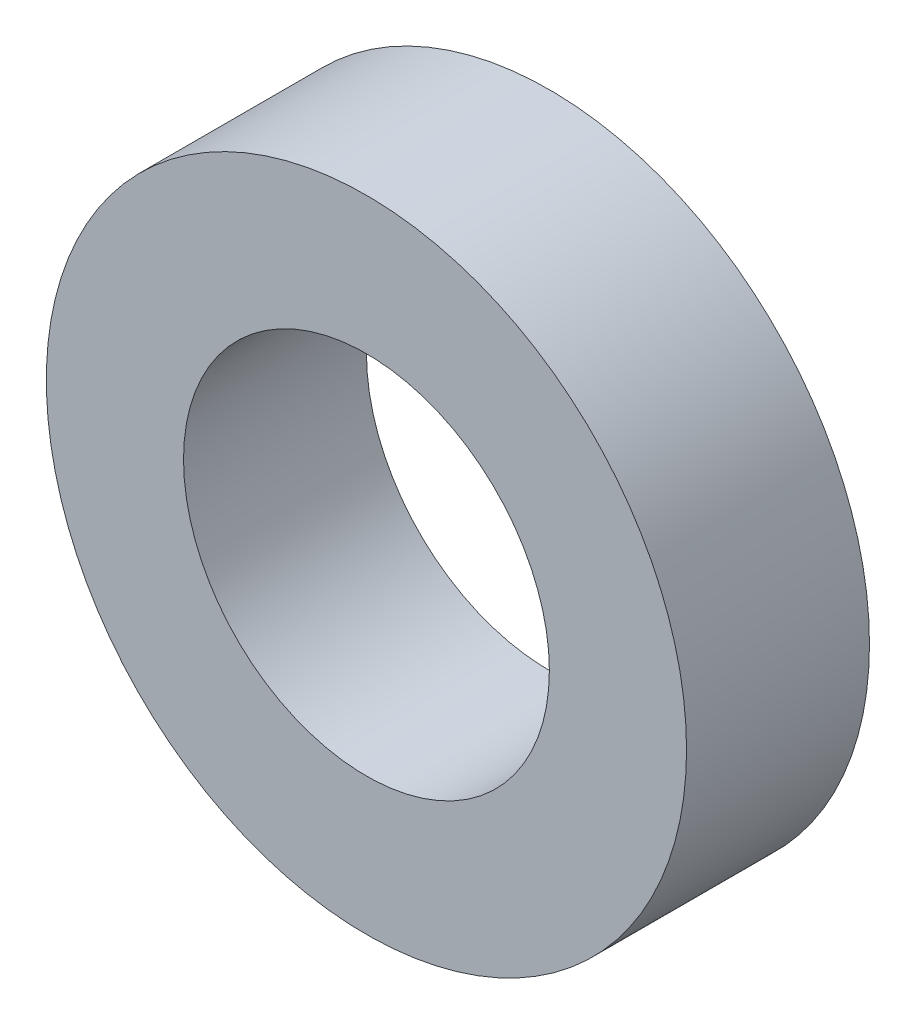
SolidWorks part; units mm, degrees
ref_plane "前视基准面" through (0, 0, 0) normal (0, 0, 1) x (1, 0, 0)
ref_plane "上视基准面" through (0, 0, 0) normal (0, 1, 0) x (1, 0, 0)
ref_plane "右视基准面" through (0, 0, 0) normal (1, 0, 0) x (0, 0, -1)
other "Configuration Table"
sketch "草图1" plane through (0, 0, 0) normal (0, 0, 1) x (1, 0, 0)
  circle A0 centre (0, 0) radius 7
  circle A1 centre (0, 0) radius 4
  dimension "D1" = 8
  dimension "D2" = 14
extrude "凸台-拉伸1" add sketch "草图1" along normal mid plane 4
